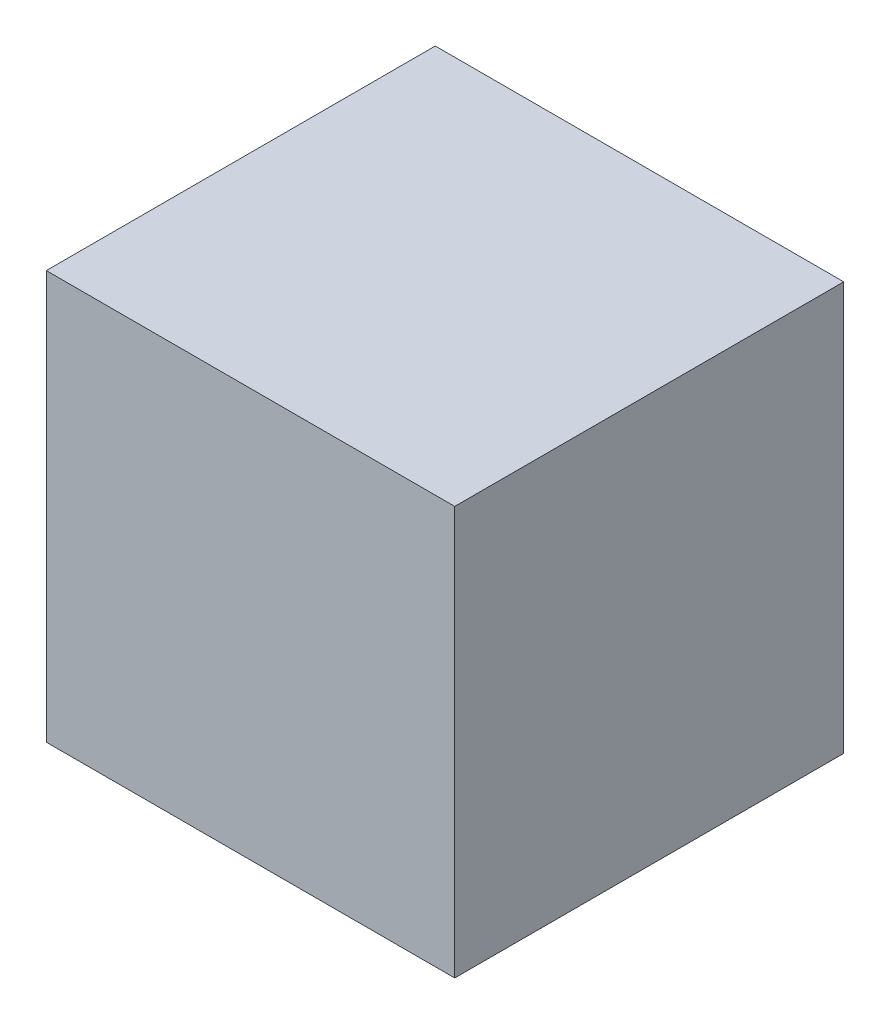
SolidWorks part; units mm, degrees
ref_plane "Alzado" through (0, 0, 0) normal (0, 0, 1) x (1, 0, 0)
ref_plane "Planta" through (0, 0, 0) normal (0, 1, 0) x (1, 0, 0)
ref_plane "Vista lateral" through (0, 0, 0) normal (1, 0, 0) x (0, 0, -1)
sketch "Croquis1" plane through (0, 0, 0) normal (0, 0, 1) x (1, 0, 0)
  line L1 (-21, -21) -> (21, -21)
  line L2 (-21, -21) -> (-21, 21)
  line L3 (-21, 21) -> (21, 21)
  line L4 (21, -21) -> (21, 21)
  line L5 (-21, -21) -> (21, 21) construction
  line L6 (-21, 21) -> (21, -21) construction
  point P0 (0, 0)
  dimension "D1" = 42
  dimension "D2" = 42
extrude "Saliente-Extruir1" add sketch "Croquis1" along normal blind 40
